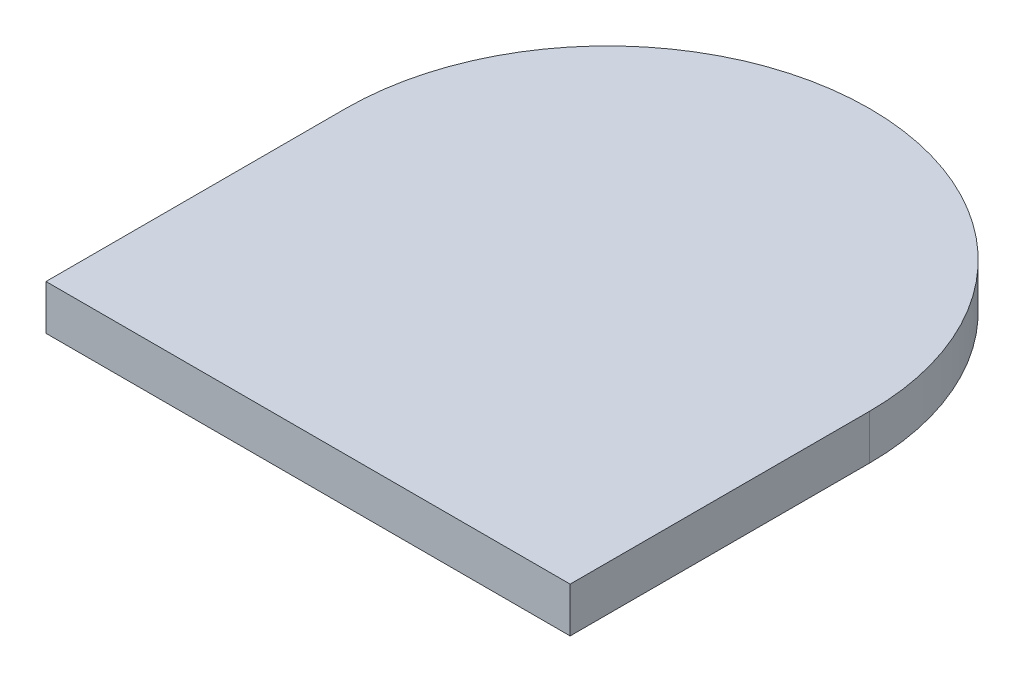
SolidWorks part; units mm, degrees
ref_plane "前视基准面" through (0, 0, 0) normal (0, 0, 1) x (1, 0, 0)
ref_plane "上视基准面" through (0, 0, 0) normal (0, 1, 0) x (1, 0, 0)
ref_plane "右视基准面" through (0, 0, 0) normal (1, 0, 0) x (0, 0, -1)
other "Configuration Table"
sketch "草图1" plane through (0, 0, 0) normal (0, 1, 0) x (1, 0, 0)
  line L0 (-17.5, 0) -> (-17.5, -20)
  line L1 (-17.5, -20) -> (17.5, -20)
  line L2 (17.5, -20) -> (17.5, 0)
  arc A0 (17.5, 0) -> (-17.5, 0) centre (0, 0) ccw
  dimension "D1" = 35
  dimension "D2" = 20
extrude "凸台-拉伸1" add sketch "草图1" along normal blind 3
